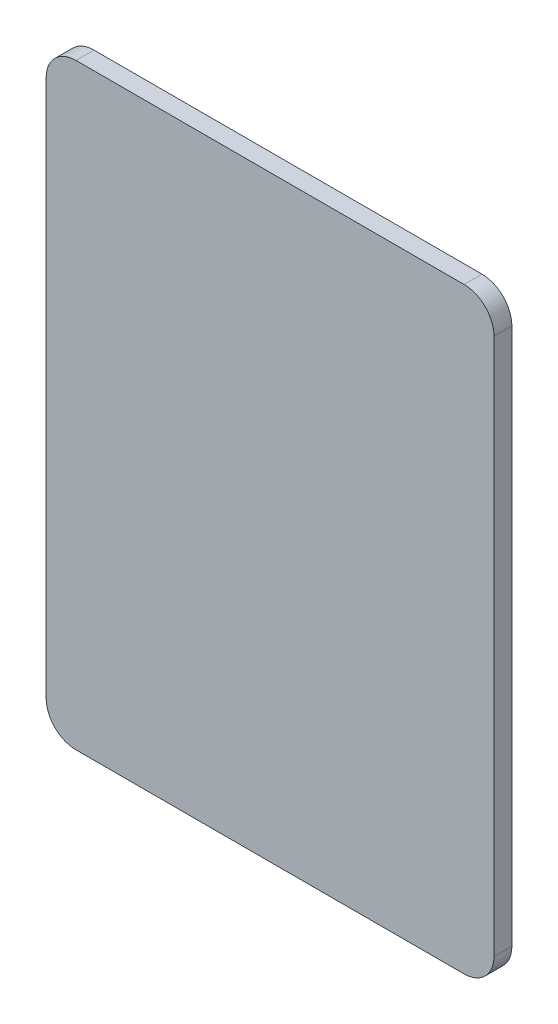
SolidWorks part; units mm, degrees
ref_plane "Front Plane" through (0, 0, 0) normal (0, 0, 1) x (1, 0, 0)
ref_plane "Top Plane" through (0, 0, 0) normal (0, 1, 0) x (1, 0, 0)
ref_plane "Right Plane" through (0, 0, 0) normal (1, 0, 0) x (0, 0, -1)
sketch "Sketch2" plane through (0, 0, 0) normal (0, 0, 1) x (1, 0, 0)
  line L1 (75, 100) -> (-75, 100)
  line L2 (75, 100) -> (75, -100)
  line L3 (75, -100) -> (-75, -100)
  line L4 (-75, 100) -> (-75, -100)
  line L5 (75, 100) -> (-75, -100) construction
  line L6 (75, -100) -> (-75, 100) construction
  point P0 (0, 0)
  dimension "D1" = 150
  dimension "D2" = 200
extrude "Boss-Extrude1" add sketch "Sketch2" along normal blind 6
fillet "Fillet1" radius 10 4 edges at (-75, -100, 3) (75, -100, 3) (-75, 100, 3) (75, 100, 3)
